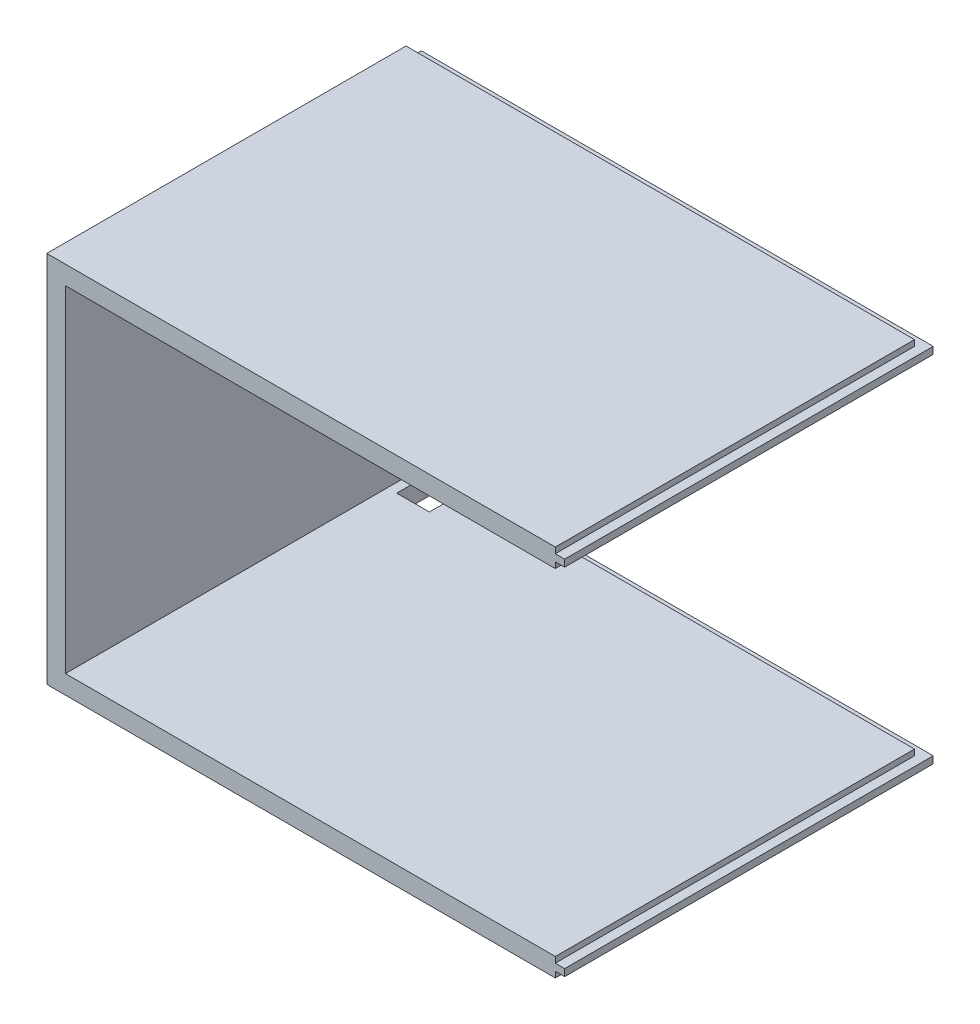
SolidWorks part; units mm, degrees
ref_plane "Ön Düzlem" through (0, 0, 0) normal (0, 0, 1) x (1, 0, 0)
ref_plane "Üst Düzlem" through (0, 0, 0) normal (0, 1, 0) x (1, 0, 0)
ref_plane "Sağ Düzlem" through (0, 0, 0) normal (1, 0, 0) x (0, 0, -1)
sketch "Çizim2" plane through (0, 0, 0) normal (0, 0, 1) x (1, 0, 0)
  line L1 (-55.5, 40) -> (55.5, 40)
  line L2 (-55.5, 40) -> (-55.5, -40)
  line L3 (-55.5, -40) -> (55.5, -40)
  line L4 (55.5, 40) -> (55.5, -40)
  line L5 (-55.5, 40) -> (55.5, -40) construction
  line L6 (-55.5, -40) -> (55.5, 40) construction
  line L7 (-51.5, 36) -> (55.5, 36)
  line L8 (-51.5, 36) -> (-51.5, -36)
  line L9 (-51.5, -36) -> (55.5, -36)
  line L10 (55.5, 36) -> (55.5, -36)
  line L11 (-51.5, 36) -> (55.5, -36) construction
  line L12 (-51.5, -36) -> (55.5, 36) construction
  point P0 (0, 0)
  point P6 (2, 0)
  dimension "D1" = 111
  dimension "D2" = 80
  dimension "D3" = 4
  dimension "D4" = 107
  dimension "D5" = 72
  dimension "D6" = 4
extrude "Yükseklik-Ekstrüzyon2" add sketch "Çizim2" against normal blind 77 contours L9 L8 L7 L4 L1 L2 L3
sketch "Çizim3" plane through (0, 0, -77) normal (0, 0, -1) x (-1, 0, 0)
  line L0 (51.5, -36) -> (-55.5, -36) construction
  line L1 (-55.5, -36) -> (-53.5, -36)
  line L2 (-55.5, -36) -> (-55.5, -37.25)
  line L3 (-55.5, -37.25) -> (-53.5, -37.25)
  line L4 (-53.5, -36) -> (-53.5, -37.25)
  line L5 (-55.5, -36) -> (-53.5, -37.25) construction
  line L6 (-55.5, -37.25) -> (-53.5, -36) construction
  line L7 (-55.5, -36) -> (-55.5, -40) construction
  line L8 (-55.5, -38.75) -> (-53.5, -38.75)
  line L9 (-55.5, -38.75) -> (-55.5, -40)
  line L10 (-55.5, -40) -> (-53.5, -40)
  line L11 (-53.5, -38.75) -> (-53.5, -40)
  line L12 (-55.5, -38.75) -> (-53.5, -40) construction
  line L13 (-55.5, -40) -> (-53.5, -38.75) construction
  line L14 (55.5, -40) -> (-55.5, -40) construction
  line L15 (-55.5, 40) -> (-53.5, 40)
  line L16 (-55.5, 40) -> (-55.5, 38.75)
  line L17 (-55.5, 38.75) -> (-53.5, 38.75)
  line L18 (-53.5, 40) -> (-53.5, 38.75)
  line L19 (-55.5, 40) -> (-53.5, 38.75) construction
  line L20 (-55.5, 38.75) -> (-53.5, 40) construction
  line L21 (-55.5, 37.25) -> (-53.5, 37.25)
  line L22 (-55.5, 37.25) -> (-55.5, 36)
  line L23 (-55.5, 36) -> (-53.5, 36)
  line L24 (-53.5, 37.25) -> (-53.5, 36)
  line L25 (-55.5, 37.25) -> (-53.5, 36) construction
  line L26 (-55.5, 36) -> (-53.5, 37.25) construction
  line L27 (55.5, 40) -> (-55.5, 40) construction
  line L28 (-55.5, 40) -> (-55.5, 36) construction
  line L29 (51.5, 36) -> (-55.5, 36) construction
  point P0 (-54.5, -36.625)
  point P9 (-54.5, -39.375)
  point P16 (-54.5, 39.375)
  point P21 (-54.5, 36.625)
  dimension "D1" = 2
  dimension "D2" = 1.25
  dimension "D3" = 0
  dimension "D4" = 0
  dimension "D5" = 2
  dimension "D6" = 1.25
  dimension "D7" = 0
  dimension "D8" = 0
  dimension "D9" = 2
  dimension "D10" = 1.25
  dimension "D11" = 2
  dimension "D12" = 1.25
  dimension "D13" = 0
  dimension "D14" = 0
  dimension "D15" = 0
  dimension "D16" = 0
extrude "Kes-Ekstrüzyon1" cut sketch "Çizim3" against normal blind 77
sketch "Çizim6" plane through (0, 0, -77) normal (0, 0, -1) x (-1, 0, 0)
  line L0 (55.5, 40) -> (55.5, -40) construction
  line L1 (-55.5, 38.75) -> (54.25, 38.75)
  line L2 (-55.5, 38.75) -> (-55.5, 37.25)
  line L3 (-55.5, 37.25) -> (54.25, 37.25)
  line L4 (54.25, 38.75) -> (54.25, 37.25)
  line L5 (-55.5, 38.75) -> (54.25, 37.25) construction
  line L6 (-55.5, 37.25) -> (54.25, 38.75) construction
  line L7 (55.5, 40) -> (-53.5, 40) construction
  line L8 (-55.5, -37.25) -> (54.25, -37.25)
  line L9 (-55.5, -37.25) -> (-55.5, -38.75)
  line L10 (-55.5, -38.75) -> (54.25, -38.75)
  line L11 (54.25, -37.25) -> (54.25, -38.75)
  line L12 (-55.5, -37.25) -> (54.25, -38.75) construction
  line L13 (-55.5, -38.75) -> (54.25, -37.25) construction
  line L14 (51.5, -36) -> (-53.5, -36) construction
  line L16 (52.75, 37.25) -> (54.25, 37.25)
  line L17 (52.75, 37.25) -> (52.75, -37.25)
  line L18 (52.75, -37.25) -> (54.25, -37.25)
  line L19 (54.25, 37.25) -> (54.25, -37.25)
  line L20 (52.75, 37.25) -> (54.25, -37.25) construction
  line L21 (52.75, -37.25) -> (54.25, 37.25) construction
  point P0 (-0.625, 38)
  point P9 (-0.625, -38)
  point P16 (53.5, 0)
  line M19 (-53.5, 38.75) -> (-55.5, 38.75)
  line M20 (-55.5, 38.75) -> (-55.5, 37.25)
  line M21 (-55.5, 37.25) -> (-53.5, 37.25)
  line M27 (-53.5, -37.25) -> (-55.5, -37.25)
  line M28 (-55.5, -37.25) -> (-55.5, -38.75)
  line M29 (-55.5, -38.75) -> (-53.5, -38.75)
  dimension "D1" = 1.5
  dimension "D2" = 1.25
  dimension "D3" = 1.25
  dimension "D4" = 109.75
  dimension "D5" = 1.5
  dimension "D6" = 109.75
  dimension "D7" = 1.25
  dimension "D8" = 1.25
  dimension "D9" = 1.5
  dimension "D10" = 1.25
  dimension "D11" = 0
  dimension "D12" = 0
extrude "Yükseklik-Ekstrüzyon3" add sketch "Çizim6" along normal blind 2 contours L4 L1 L3 M19 M20 M21 | L19 L3 L17 L8 | L11 L8 L10 M27 M28 M29
sketch "Çizim7" plane through (0, -40, 0) normal (0, -1, 0) x (1, 0, 0)
  line L0 (-55.5, -77) -> (-55.5, 0) construction
  line L1 (-49.5, -69) -> (-42.5, -69)
  line L2 (-49.5, -69) -> (-49.5, -79)
  line L3 (-49.5, -79) -> (-42.5, -79)
  line L4 (-42.5, -69) -> (-42.5, -79)
  line L5 (-49.5, -69) -> (-42.5, -79) construction
  line L6 (-49.5, -79) -> (-42.5, -69) construction
  line L8 (53.5, -77) -> (-54.25, -77) construction
  point P0 (-46, -74)
  dimension "D1" = 7
  dimension "D2" = 10
  dimension "D3" = 6
  dimension "D4" = 8
extrude "Kes-Ekstrüzyon2" cut sketch "Çizim7" against normal blind 10
